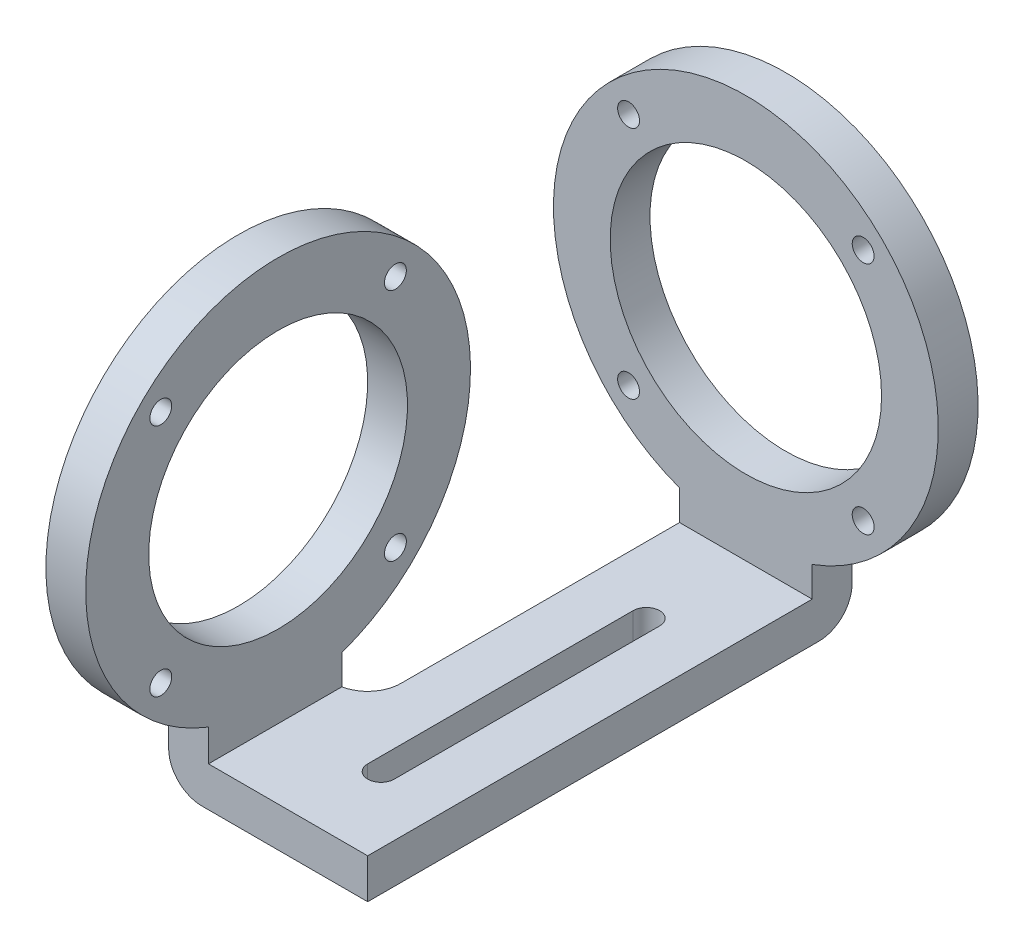
SolidWorks part; units mm, degrees
ref_plane "Front Plane" through (0, 0, 0) normal (0, 0, 1) x (1, 0, 0)
ref_plane "Top Plane" through (0, 0, 0) normal (0, 1, 0) x (1, 0, 0)
ref_plane "Right Plane" through (0, 0, 0) normal (1, 0, 0) x (0, 0, -1)
sketch "Sketch1" plane through (0, 0, 0) normal (0, 0, 1) x (1, 0, 0)
  line L0 (0, 0) -> (0, 29) construction
  line L1 (0, 29) -> (0, -29) construction
  line L2 (0, 0) -> (17.68, 0) construction
  line L3 (17.68, 0) -> (17.68, -17.68) construction
  line L7 (0, 0) -> (0, -17.62) construction
  circle A0 centre (0, 0) radius 29
  circle A5 centre (0, 0) radius 20.45
  circle A6 centre (17.68, -17.68) radius 1.65
  circle A9 centre (-17.68, -17.68) radius 1.65
  circle A10 centre (-17.68, 17.68) radius 1.65
  circle A11 centre (17.68, 17.68) radius 1.65
  point P15 (0.0273, 0.0327)
  point P19 (0, 0)
  dimension "D1" = 58
  dimension "D2" = 4
  dimension "D6" = 40.9
extrude "Boss-Extrude1" add sketch "Sketch1" along normal blind 6
sketch "Sketch3" plane through (0, 0, 6) normal (0, 0, 1) x (1, 0, 0)
  line L0 (0, 0) -> (0, -40.0185) construction
  line L6 (0, -25.7485) -> (-10, -25.7485)
  line L7 (-10, -25.7485) -> (-10, -37.7485)
  line L8 (-10, -37.7485) -> (10, -37.7485)
  line L9 (10, -37.7485) -> (10, -25.7485)
  line L10 (10, -25.7485) -> (0, -25.7485)
  point P3 (0, -29)
  dimension "D1" = 10
  dimension "D2" = 10
  dimension "D3" = 12
extrude "Boss-Extrude3" add sketch "Sketch3" against normal blind 6
sketch "Sketch4" plane through (0, 0, 6) normal (0, 0, 1) x (1, 0, 0)
  line L0 (10, -37.7485) -> (10, -27.2213) construction
  line L1 (-10, -37.7485) -> (10, -37.7485)
  line L2 (-10, -37.7485) -> (-10, -31.7485)
  line L3 (-10, -31.7485) -> (10, -31.7485)
  line L4 (10, -37.7485) -> (10, -31.7485)
  dimension "D1" = 6
extrude "Boss-Extrude4" add sketch "Sketch4" along normal blind 67
sketch "Sketch5" plane through (-10, 0, 0) normal (-1, 0, 0) x (0, 0, 1)
  line L0 (0, -37.7485) -> (73, -37.7485) construction
  line L1 (73, -31.7485) -> (53, -31.7485)
  line L2 (73, -31.7485) -> (73, -37.7485)
  line L3 (73, -37.7485) -> (53, -37.7485)
  line L4 (53, -31.7485) -> (53, -37.7485)
  dimension "D1" = 20
extrude "Boss-Extrude5" add sketch "Sketch5" along normal blind 10
sketch "Sketch7" plane through (-20, 0, 0) normal (-1, 0, 0) x (0, 0, 1)
  line L0 (62.5038, 0.0874) -> (62.5038, -43.6092) construction
  circle A0 centre (62.5038, 0.0874) radius 29
  circle A6 centre (80.1838, -17.5926) radius 1.65
  circle A7 centre (44.8238, -17.5926) radius 1.65
  circle A9 centre (44.8238, 17.7674) radius 1.65
  circle A11 centre (80.1838, 17.7674) radius 1.65
  circle A13 centre (62.5038, 0.0874) radius 19.5
  point P17 (62.505, 0.0885)
  point P20 (62.5038, 0.0874)
  dimension "D1" = 4
extrude "Boss-Extrude6" add sketch "Sketch7" against normal blind 6 separate body
sketch "Sketch8" plane through (0, -31.7485, 0) normal (0, 1, 0) x (1, 0, 0)
  line L0 (10, -73) -> (-20, -73) construction
  line L1 (-20, -53) -> (-14, -53)
  line L2 (-20, -53) -> (-20, -73)
  line L3 (-20, -73) -> (-14, -73)
  line L4 (-14, -53) -> (-14, -73)
  dimension "D1" = 6
extrude "Boss-Extrude8" add sketch "Sketch8" along normal blind 6
sketch "Sketch9" plane through (0, -37.7485, 0) normal (0, -1, 0) x (1, 0, 0)
  line L0 (0, 0) -> (0, 73) construction
  line L1 (-10, 0) -> (10, 0) construction
  line L2 (-20, 73) -> (10, 73) construction
  line L3 (-10, 53) -> (-10, 73) construction
  line L4 (-10, 63) -> (10, 63) construction
  line L5 (0, 61) -> (0, 21) construction
  line L6 (2, 61) -> (2, 21)
  line L7 (-2, 61) -> (-2, 21)
  line L8 (10, 0) -> (10, 73) construction
  arc A0 (2, 61) -> (-2, 61) centre (0, 61) ccw
  arc A1 (-2, 21) -> (2, 21) centre (0, 21) ccw
  point P12 (0, 41)
  point P20 (0, 63)
  dimension "D2" = 2
  dimension "D1" = 40
extrude "Cut-Extrude1" cut sketch "Sketch9" against normal blind 6
fillet "Fillet1" radius 5 2 edges at (0, -37.7485, 0) (-20, -37.7485, 63)
fillet "Fillet2" radius 5 1 edges at (-10, -34.7485, 53)
